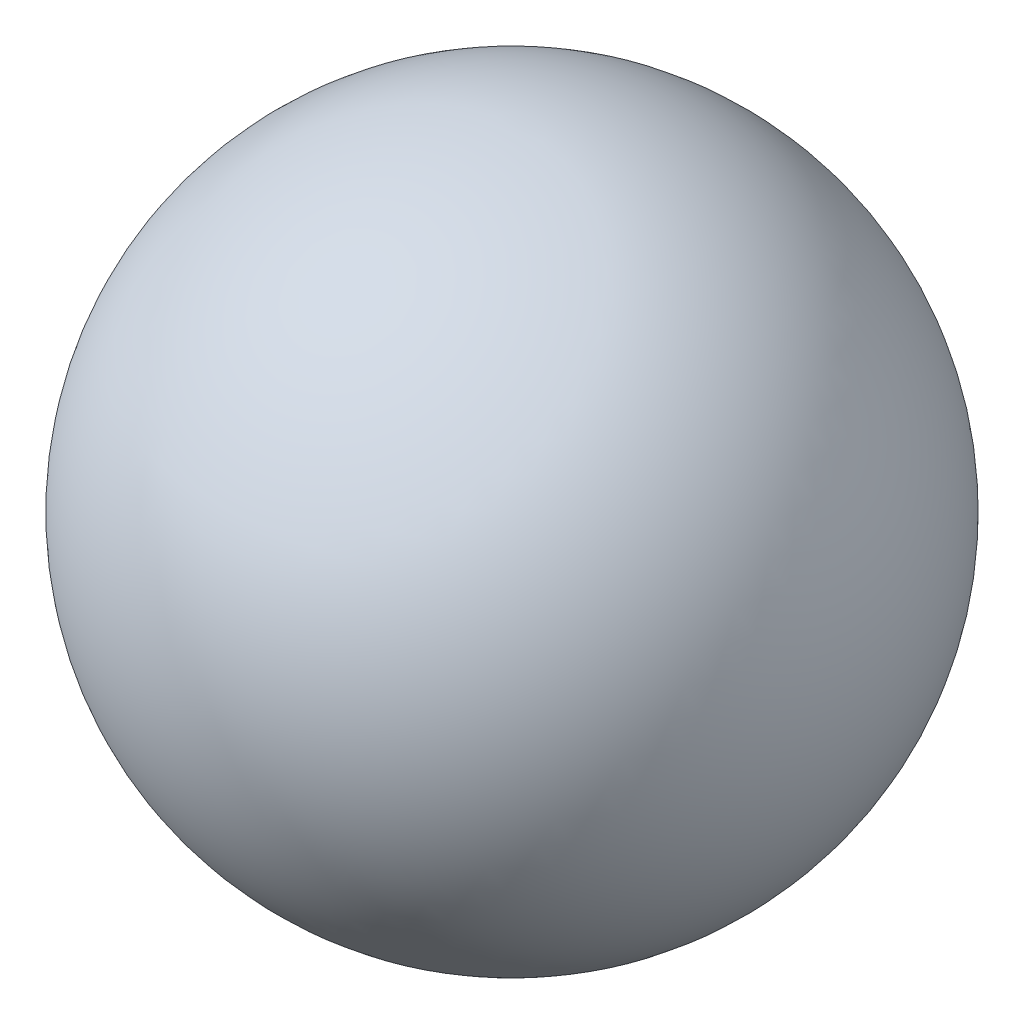
SolidWorks part; units mm, degrees
ref_plane "前视基准面" through (0, 0, 0) normal (0, 0, 1) x (1, 0, 0)
ref_plane "上视基准面" through (0, 0, 0) normal (0, 1, 0) x (1, 0, 0)
ref_plane "右视基准面" through (0, 0, 0) normal (1, 0, 0) x (0, 0, -1)
sketch "草图1" plane through (0, 0, 0) normal (0, 0, 1) x (1, 0, 0)
  line L0 (0, 0) -> (0, 50000) construction
  circle A0 centre (0, 0) radius 75
sketch "草图2" plane through (0, 0, 0) normal (1, 0, 0) x (0, 0, -1)
  line L0 (0, 0) -> (-50000, 0) construction
  line L1 (0, 75) -> (0, -75) construction
  point P4 (0, 0)
revolve "旋转1" add sketch "草图1" angle 360 about L0
